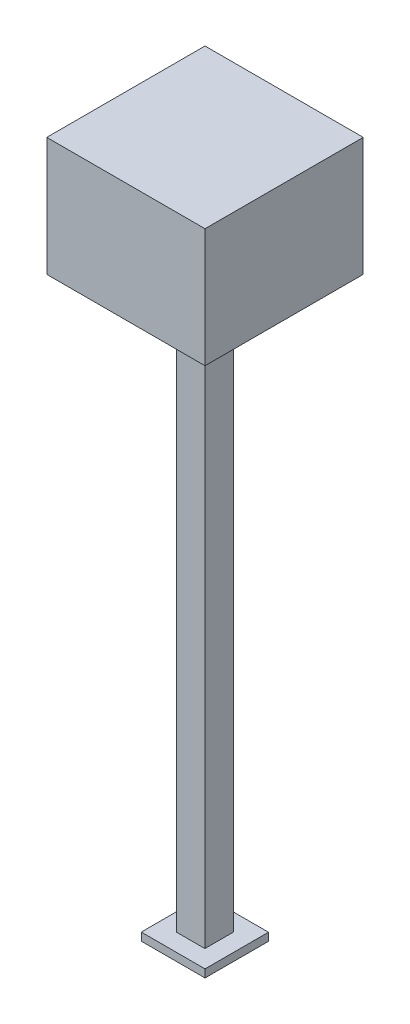
SolidWorks part; units mm, degrees
ref_plane "Front Plane" through (0, 0, 0) normal (0, 0, 1) x (1, 0, 0)
ref_plane "Top Plane" through (0, 0, 0) normal (0, 1, 0) x (1, 0, 0)
ref_plane "Right Plane" through (0, 0, 0) normal (1, 0, 0) x (0, 0, -1)
sketch "Sketch1" plane through (0, 0, 0) normal (0, 1, 0) x (1, 0, 0)
  line L1 (0, 0) -> (-18, 0)
  line L2 (0, 0) -> (0, 18)
  line L3 (0, 18) -> (-18, 18)
  line L4 (-18, 0) -> (-18, 18)
  dimension "D1" = 18
extrude "Boss-Extrude1" add sketch "Sketch1" along normal blind 360
sketch "Sketch2" plane through (0, 360, 0) normal (0, 1, 0) x (1, 0, 0)
  line L1 (41.0386, -40.9633) -> (-58.9614, -40.9633)
  line L2 (41.0386, -40.9633) -> (41.0386, 59.0367)
  line L3 (41.0386, 59.0367) -> (-58.9614, 59.0367)
  line L4 (-58.9614, -40.9633) -> (-58.9614, 59.0367)
  line L5 (41.0386, -40.9633) -> (-58.9614, 59.0367) construction
  line L6 (41.0386, 59.0367) -> (-58.9614, -40.9633) construction
  point P0 (-8.9614, 9.0367)
  point P5 (-8.9614, 9.0367)
  dimension "D1" = 100
  dimension "D2" = 100
extrude "Boss-Extrude2" add sketch "Sketch2" along normal blind 75
sketch "Sketch3" plane through (0, 0, 0) normal (0, -1, 0) x (-1, 0, 0)
  line L0 (18, 18) -> (18, 0) construction
  line L1 (-11.1457, 29.0574) -> (29.1457, 29.0574)
  line L2 (-11.1457, 29.0574) -> (-11.1457, -11.0574)
  line L3 (-11.1457, -11.0574) -> (29.1457, -11.0574)
  line L4 (29.1457, 29.0574) -> (29.1457, -11.0574)
  line L5 (-11.1457, 29.0574) -> (29.1457, -11.0574) construction
  line L6 (-11.1457, -11.0574) -> (29.1457, 29.0574) construction
  line L8 (18, 0) -> (0, 0) construction
  point P0 (9, 9)
  point P5 (0, 0)
  point P8 (18, 9)
  point P9 (9.0275, 8.9232)
  point P12 (0, 0)
  point P13 (9, 0)
extrude "Boss-Extrude3" add sketch "Sketch3" along normal blind 5
